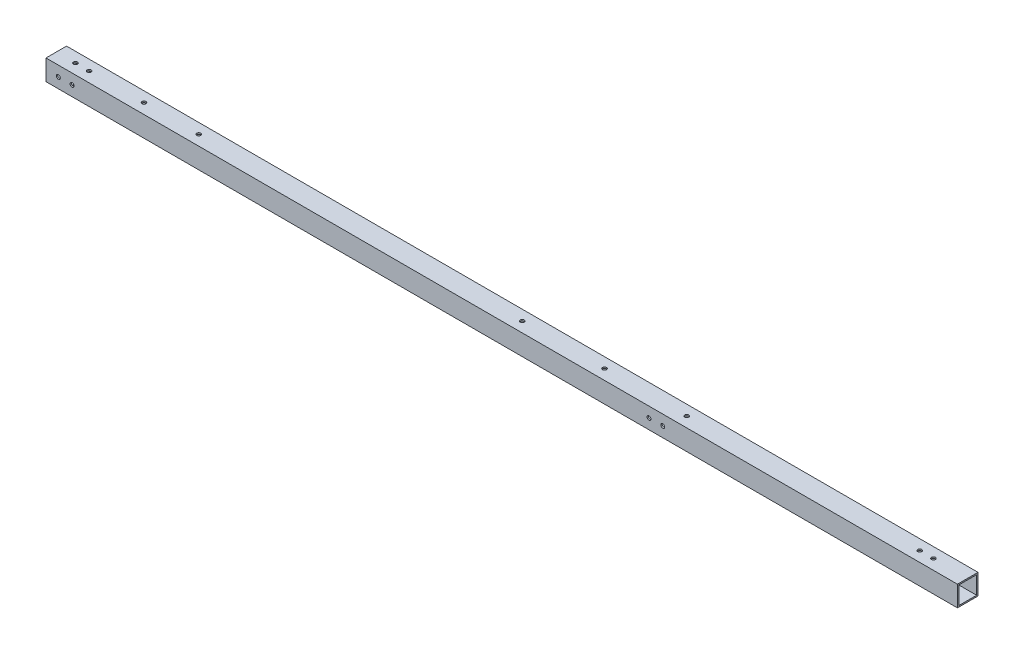
SolidWorks part; units mm, degrees
material "Thornel Mat VMA"
ref_plane "前视基准面" through (0, 0, 0) normal (0, 0, 1) x (1, 0, 0)
ref_plane "上视基准面" through (0, 0, 0) normal (0, 1, 0) x (1, 0, 0)
ref_plane "右视基准面" through (0, 0, 0) normal (1, 0, 0) x (0, 0, -1)
other "Configuration Table"
sketch "草图1" plane through (0, 0, 0) normal (1, 0, 0) x (0, 0, -1)
  line L0 (-6.5, -6.5) -> (-6.5, 6.5)
  line L1 (-7.5, -7.5) -> (7.5, -7.5)
  line L2 (-7.5, -7.5) -> (-7.5, 7.5)
  line L3 (-7.5, 7.5) -> (7.5, 7.5)
  line L4 (7.5, -7.5) -> (7.5, 7.5)
  line L5 (-7.5, -7.5) -> (7.5, 7.5) construction
  line L6 (-7.5, 7.5) -> (7.5, -7.5) construction
  line L7 (-6.5, 6.5) -> (6.5, 6.5)
  line L8 (6.5, -6.5) -> (6.5, 6.5)
  line L9 (-6.5, -6.5) -> (6.5, -6.5)
  point P0 (0, 0)
  dimension "D1" = 15
  dimension "D2" = 15
  dimension "D3" = 1
extrude "凸台-拉伸1" add sketch "草图1" along normal blind 665
sketch "草图3" plane through (0, 0, -7.5) normal (0, 0, -1) x (-1, 0, 0)
  circle A0 centre (-9, 0) radius 1.45 construction
  circle A1 centre (-19, 0) radius 1.45 construction
  circle A2 centre (-440, 0) radius 1.45 construction
  circle A3 centre (-450, 0) radius 1.45 construction
  circle A4 centre (-9, 0) radius 1.45
  circle A5 centre (-19, 0) radius 1.45
  circle A6 centre (-440, 0) radius 1.45
  circle A7 centre (-450, 0) radius 1.45
extrude "切除-拉伸1" cut sketch "草图3" against normal through all
sketch "草图4" plane through (0, 7.5, 0) normal (0, 1, 0) x (1, 0, 0)
  circle A0 centre (630, 0) radius 1.45 construction
  circle A1 centre (640, 0) radius 1.45 construction
  circle A2 centre (14, 0) radius 1.45 construction
  circle A3 centre (24, 0) radius 1.45 construction
  circle A4 centre (64, 0) radius 1.45 construction
  circle A5 centre (104, 0) radius 1.45 construction
  circle A6 centre (340, 0) radius 1.45 construction
  circle A7 centre (400, 0) radius 1.45 construction
  circle A8 centre (460, 0) radius 1.45 construction
  circle A9 centre (630, 0) radius 1.45
  circle A10 centre (640, 0) radius 1.45
  circle A11 centre (14, 0) radius 1.45
  circle A12 centre (24, 0) radius 1.45
  circle A13 centre (64, 0) radius 1.45
  circle A14 centre (104, 0) radius 1.45
  circle A15 centre (340, 0) radius 1.45
  circle A16 centre (400, 0) radius 1.45
  circle A17 centre (460, 0) radius 1.45
extrude "切除-拉伸2" cut sketch "草图4" against normal through all
